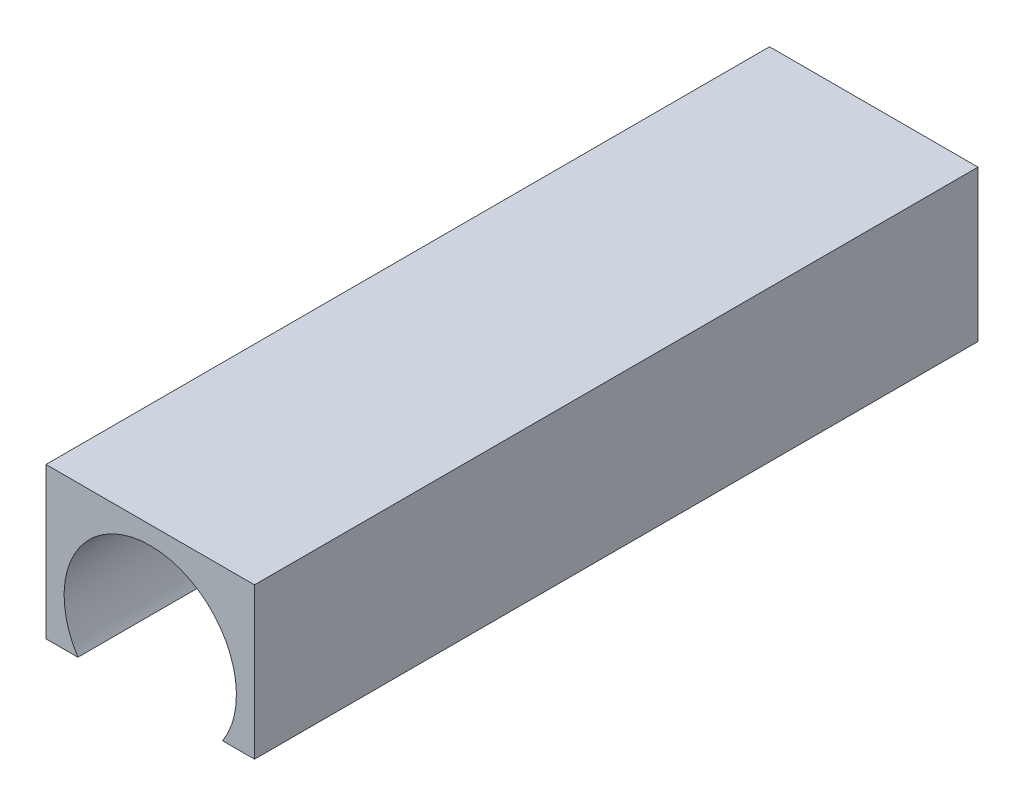
SolidWorks part; units mm, degrees
ref_plane "Front Plane" through (0, 0, 0) normal (0, 0, 1) x (1, 0, 0)
ref_plane "Top Plane" through (0, 0, 0) normal (0, 1, 0) x (1, 0, 0)
ref_plane "Right Plane" through (0, 0, 0) normal (1, 0, 0) x (0, 0, -1)
sketch "Sketch1" plane through (0, 0, 0) normal (0, 0, 1) x (1, 0, 0)
  line L0 (0, 0) -> (1.12, 0)
  line L1 (0.635, 1.6429) -> (6.685, 1.6429) construction
  line L2 (0, 0) -> (0, 5.3029)
  line L3 (0, 5.3029) -> (7.32, 5.3029)
  line L4 (0, 5.3029) -> (3.66, 1.6429) construction
  line L5 (6.2, 0) -> (7.32, 0)
  line L6 (7.32, 0) -> (7.32, 5.3029)
  line L7 (3.66, 1.6429) -> (7.32, 5.3029) construction
  arc A0 (1.12, 0) -> (6.2, 0) centre (3.66, 1.6429) cw
  dimension "D1" = 6.05
  dimension "D2" = 5.08
  dimension "D3" = 0.635
extrude "Boss-Extrude1" add sketch "Sketch1" along normal mid plane 25.4
